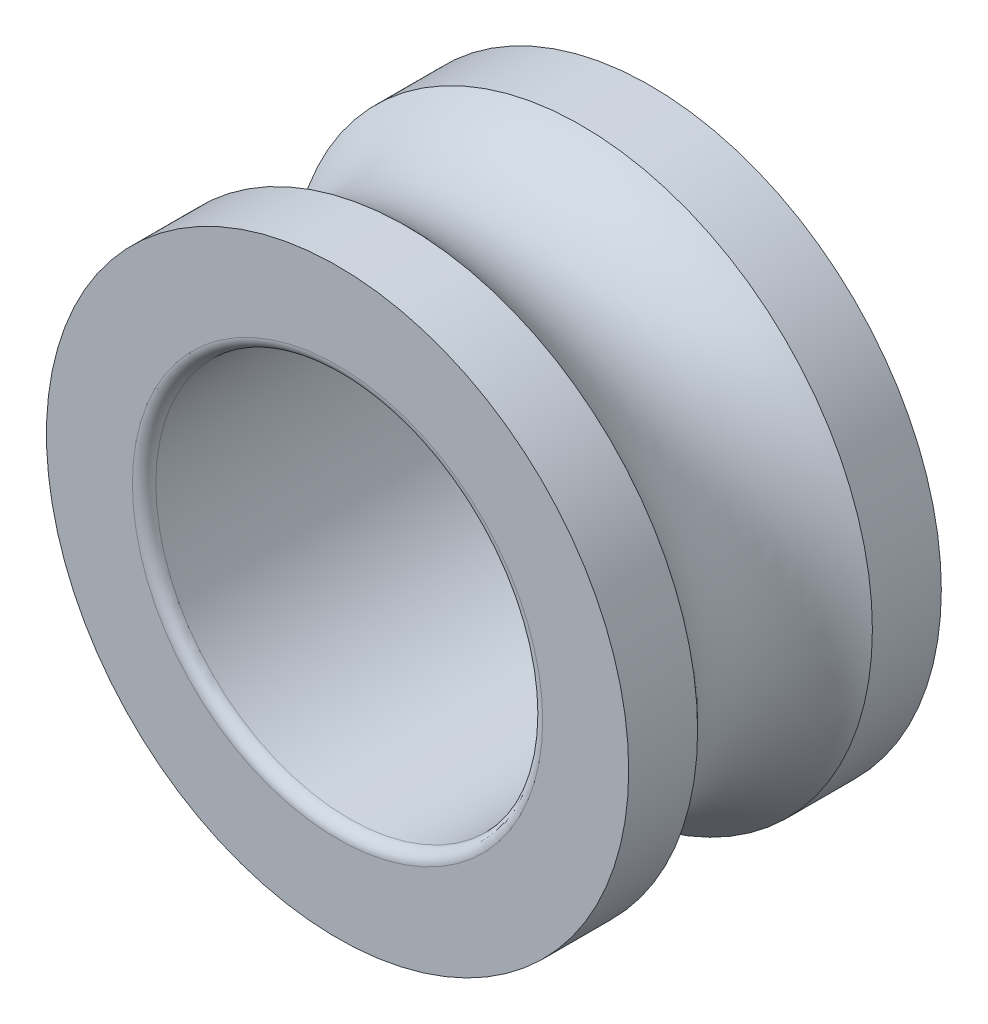
SolidWorks part; units mm, degrees
material "Plain Carbon Steel"
ref_plane "Front Plane" through (0, 0, 0) normal (0, 0, 1) x (1, 0, 0)
ref_plane "Top Plane" through (0, 0, 0) normal (0, 1, 0) x (1, 0, 0)
ref_plane "Right Plane" through (0, 0, 0) normal (1, 0, 0) x (0, 0, -1)
sketch "Sketch1" plane through (0, 0, 0) normal (1, 0, 0) x (0, 0, -1)
  line L0 (-7.4194, 0) -> (6.8548, 0) construction
  line L1 (0, 6.45) -> (2.072, 6.45) construction
  line L2 (-4, 7.45) -> (-2.2361, 7.45)
  line L3 (-4, 7.45) -> (-4, 5.25)
  line L4 (-3.7, 4.95) -> (3.7, 4.95)
  line L5 (4, 7.45) -> (4, 5.25)
  line L6 (-4, 7.45) -> (4, 4.95) construction
  line L7 (-4, 4.95) -> (4, 7.45) construction
  line L8 (2.2361, 7.45) -> (4, 7.45)
  arc A0 (2.2361, 7.45) -> (-2.2361, 7.45) centre (0, 9.45) cw
  arc A1 (-4, 5.25) -> (-3.7, 4.95) centre (-3.7, 5.25) ccw
  arc A2 (3.7, 4.95) -> (4, 5.25) centre (3.7, 5.25) ccw
  point P3 (0, 6.2)
  dimension "D4" = 3
  dimension "D6" = 0.3
  dimension "D1" = 4.95
  dimension "D2" = 8
  dimension "D3" = 2.5
  dimension "D5" = 1
revolve "Revolve1" add sketch "Sketch1" angle 360 about L0
